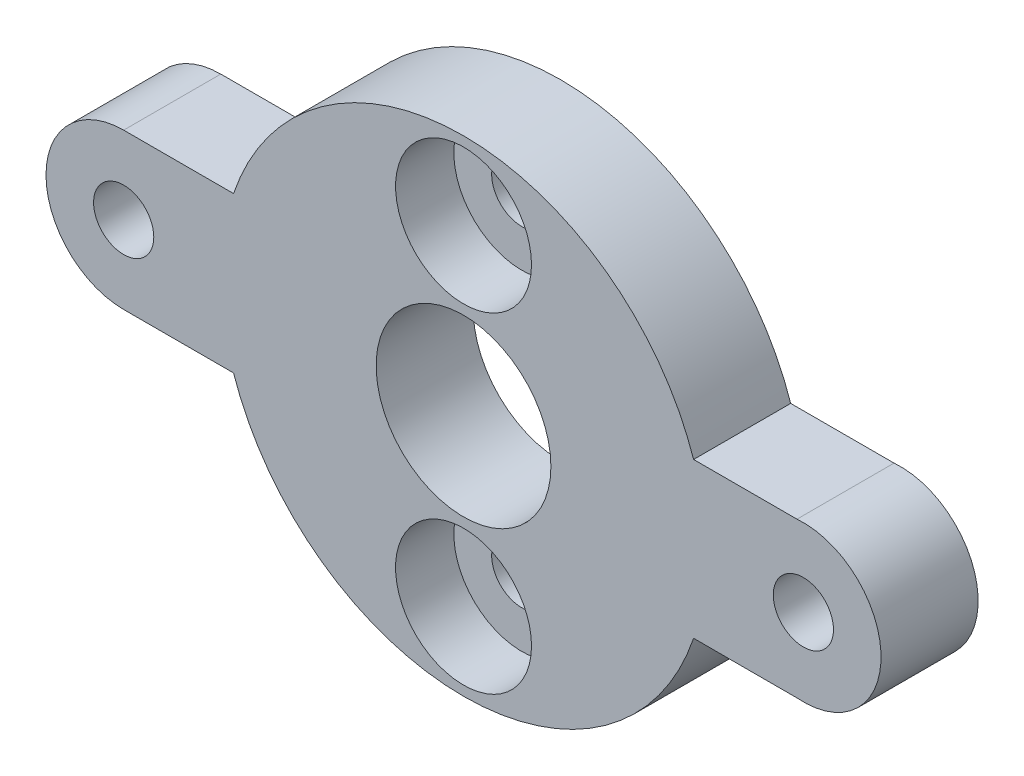
SolidWorks part; units mm, degrees
ref_plane "Front Plane" through (0, 0, 0) normal (0, 0, 1) x (1, 0, 0)
ref_plane "Top Plane" through (0, 0, 0) normal (0, 1, 0) x (1, 0, 0)
ref_plane "Right Plane" through (0, 0, 0) normal (1, 0, 0) x (0, 0, -1)
sketch "Sketch1" plane through (0, 0, 0) normal (0, 0, 1) x (1, 0, 0)
  line L0 (-17.5, 0) -> (17.5, 0) construction
  line L1 (0, -8.5) -> (0, 8.5) construction
  line L2 (-17.5, 4) -> (-11.8427, 4)
  line L3 (-17.5, -4) -> (-11.8427, -4)
  line L4 (17.17, 3.9864) -> (11.8473, 3.9864)
  line L5 (17.17, -3.9864) -> (11.8473, -3.9864)
  circle A0 centre (-17.5, 0) radius 1.55
  circle A1 centre (17.5, 0) radius 1.55
  arc A2 (-17.5, 4) -> (-17.5, -4) centre (-17.5, 0) ccw
  arc A3 (17.17, 3.9864) -> (17.17, -3.9864) centre (17.5, 0) cw
  circle A4 centre (0, 0) radius 4.5
  arc A5 (-11.8427, 4) -> (11.8473, 3.9864) centre (0, 0) cw
  arc A6 (-11.8427, -4) -> (11.8473, -3.9864) centre (0, 0) ccw
  circle A7 centre (0, 8.5) radius 1.55
  circle A8 centre (0, -8.5) radius 1.55
  circle A9 centre (0, 0) radius 12.5 construction
  point P4 (0, 0)
  point P18 (0, 0)
  point P25 (0, 0)
extrude "Boss-Extrude1" add sketch "Sketch1" along normal blind 5
sketch "Sketch2" plane through (0, 0, 5) normal (0, 0, 1) x (1, 0, 0)
  circle A0 centre (0, 8.5) radius 3.5
  circle A1 centre (0, -8.5) radius 3.5
extrude "Cut-Extrude1" cut sketch "Sketch2" against normal blind 3
